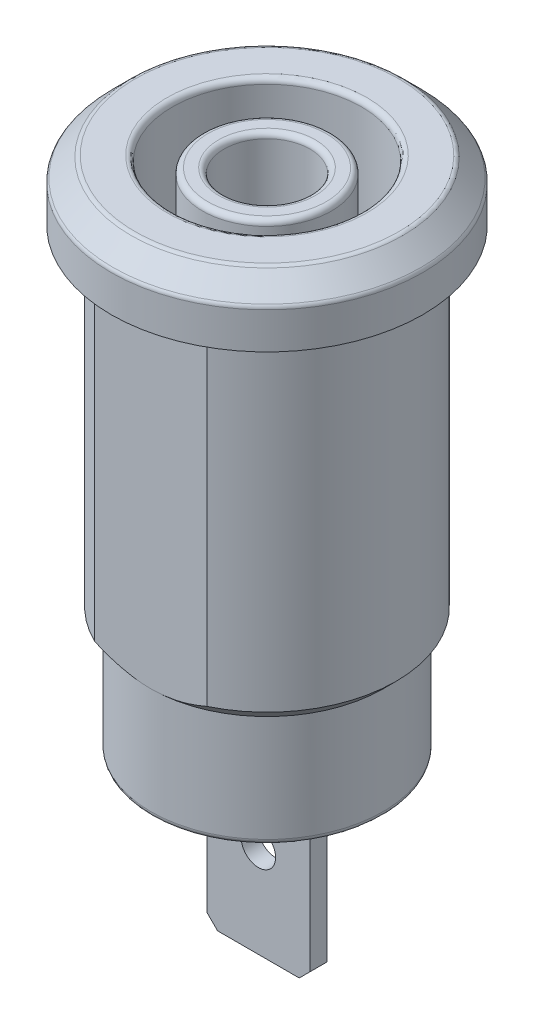
SolidWorks part; units mm, degrees
ref_plane "Front Plane" through (0, 0, 0) normal (0, 0, 1) x (1, 0, 0)
ref_plane "Top Plane" through (0, 0, 0) normal (0, 1, 0) x (1, 0, 0)
ref_plane "Right Plane" through (0, 0, 0) normal (1, 0, 0) x (0, 0, -1)
sketch "Sketch1" plane through (0, 0, 0) normal (0, 0, 1) x (1, 0, 0)
  line L1 (-6.25, 0) -> (-7.25, -1)
  line L2 (-7.25, -1) -> (-7.25, -2.8)
  line L3 (-7.25, -2.8) -> (-6, -2.8)
  line L4 (-6, -2.8) -> (-6, -18.2)
  line L5 (-6, -18.2) -> (-5.4, -18.8)
  line L6 (-5.4, -18.8) -> (-5.4, -24)
  line L7 (-5.4, -24) -> (0, -24)
  line L8 (0, -24) -> (0, 0) construction
  line L9 (-2, -0.5) -> (-2, -20)
  line L10 (-2, -20) -> (0, -21.1547)
  line L11 (0, -21.1547) -> (0, -24)
  line L12 (-4.4, 0) -> (-4.4, -21.5)
  line L13 (-4.4, -21.5) -> (-3, -21.5)
  line L14 (-3, -21.5) -> (-3, -0.5)
  line L15 (-4.4, 0) -> (-6.25, 0)
  line L16 (-3, -0.5) -> (-2, -0.5)
  dimension "D1" = 14.5
  dimension "D2" = 24
  dimension "D3" = 16
  dimension "D4" = 2.8
  dimension "D5" = 10.8
  dimension "D6" = 12
  dimension "D7" = 1
  dimension "D8" = 0.5
  dimension "D9" = 4
  dimension "D10" = 60
  dimension "D11" = 45
  dimension "D12" = 1
  dimension "D13" = 1
  dimension "D14" = 2.5
  dimension "D15" = 19.5
revolve "Revolve1" add sketch "Sketch1" angle 360 about L8
sketch "Sketch2" plane through (0, 0, 0) normal (0, 0, 1) x (1, 0, 0)
  line L0 (-2.4, -24) -> (-2.4, -31.5)
  line L1 (-5.4, -24) -> (5.4, -24) construction
  line L2 (-2.4, -31.5) -> (-1.9, -32)
  line L3 (-1.9, -32) -> (1.9, -32)
  line L4 (1.9, -32) -> (2.4, -31.5)
  line L5 (2.4, -31.5) -> (2.4, -24)
  line L6 (2.4, -24) -> (-2.4, -24)
  line L7 (0, -24) -> (0, 0) construction
  circle A0 centre (0, -27.7) radius 0.8
  point P13 (0, 0)
  dimension "D5" = 4.3
  dimension "D6" = 1.6
  dimension "D1" = 45
  dimension "D2" = 4.8
  dimension "D3" = 8
  dimension "D4" = 0.5
extrude "Boss-Extrude1" add sketch "Sketch2" along normal mid plane 0.8
sketch "Sketch3" plane through (0, -24, 0) normal (0, -1, 0) x (1, 0, 0)
  line L0 (2.6153, 5.4) -> (-2.6153, 5.4)
  line L1 (-2.6153, -5.4) -> (2.6153, -5.4)
  circle A0 centre (0, 0) radius 6 construction
  arc A1 (-2.6153, 5.4) -> (-2.6153, -5.4) centre (0, 0) ccw
  arc A2 (2.6153, -5.4) -> (2.6153, 5.4) centre (0, 0) ccw
  dimension "D1" = 10.8
extrude "Cut-Extrude1" cut sketch "Sketch3" against normal up to surface (21.2 mm away) flip side to cut up to face at (0, -2.8, -6)
fillet "Fillet1" radius 0.25 9 edges at (0, -24, -5.4) (0, -20, -2) (0, -21.5, -3) (0, -21.5, -4.4) (0, 0, -4.4) (0, 0, -6.25) (0, -0.5, -2) (0, -0.5, -3) (0, -1, -7.25)
